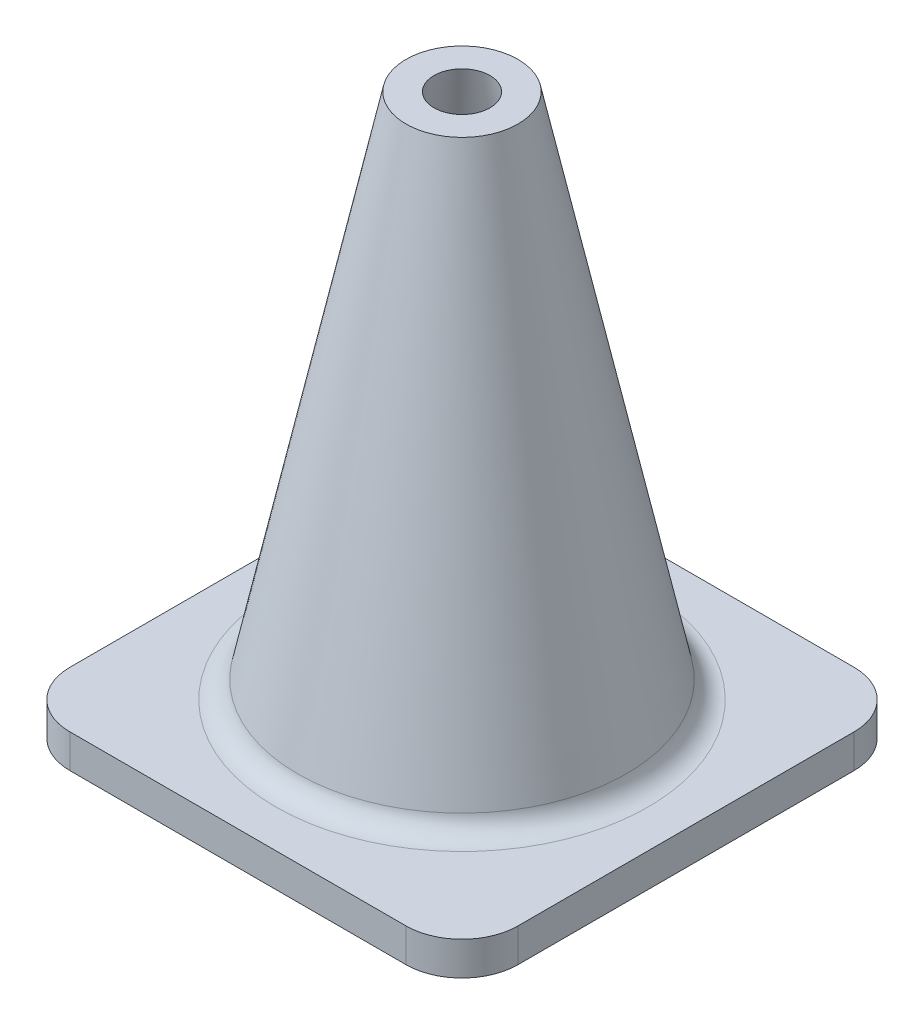
SolidWorks part; units mm, degrees
ref_plane "Front Plane" through (0, 0, 0) normal (0, 0, 1) x (1, 0, 0)
ref_plane "Top Plane" through (0, 0, 0) normal (0, 1, 0) x (1, 0, 0)
ref_plane "Right Plane" through (0, 0, 0) normal (1, 0, 0) x (0, 0, -1)
sketch "Sketch2" plane through (0, 0, 0) normal (0, 1, 0) x (1, 0, 0)
  line L1 (-20, 20) -> (20, 20)
  line L2 (-20, 20) -> (-20, -20)
  line L3 (-20, -20) -> (20, -20)
  line L4 (20, 20) -> (20, -20)
  line L5 (-20, 20) -> (20, -20) construction
  line L6 (-20, -20) -> (20, 20) construction
  point P0 (0, 0)
  dimension "D1" = 40
extrude "Boss-Extrude1" add sketch "Sketch2" along normal blind 3
sketch "Sketch3" plane through (0, 0, 0) normal (0, 0, 1) x (1, 0, 0)
  line L0 (-15, 3) -> (-5, 50)
  line L1 (-5, 50) -> (-2.5, 50)
  line L2 (-2.5, 50) -> (-12.5, 3)
  line L3 (-12.5, 3) -> (-15, 3)
  line L4 (22, 0) -> (-22, 0) construction
  line L5 (-20, 3) -> (20, 3) construction
  line L6 (-20, 3) -> (-20, 0) construction
  line L7 (0, -22) -> (0, 22) construction
  dimension "D1" = 50
  dimension "D2" = 5
  dimension "D3" = 2.5
  dimension "D4" = 2.5
ref_axis "Axis1" through (0, -2.5, 0) along (0, 1, 0)
revolve "Revolve1" add sketch "Sketch3" angle 360 about axis through (0, -2.5, 0) along (0, 1, 0)
fillet "Fillet1" radius 5 4 edges at (20, 1.5, 20) (-20, 1.5, -20) (20, 1.5, -20) (-20, 1.5, 20)
sketch "Sketch4" plane through (0, 0, 0) normal (0, -1, 0) x (1, 0, 0)
  circle A0 centre (0, 0) radius 12.5
  dimension "D1" = 25
extrude "Cut-Extrude1" cut sketch "Sketch4" against normal up to next
fillet "Fillet2" radius 5 1 edges at (0, 3, -12.5)
fillet "Fillet3" radius 2 1 edges at (0, 3, -15)
fillet "Fillet4" radius 0.5 1 edges at (0, 0, -12.5)
